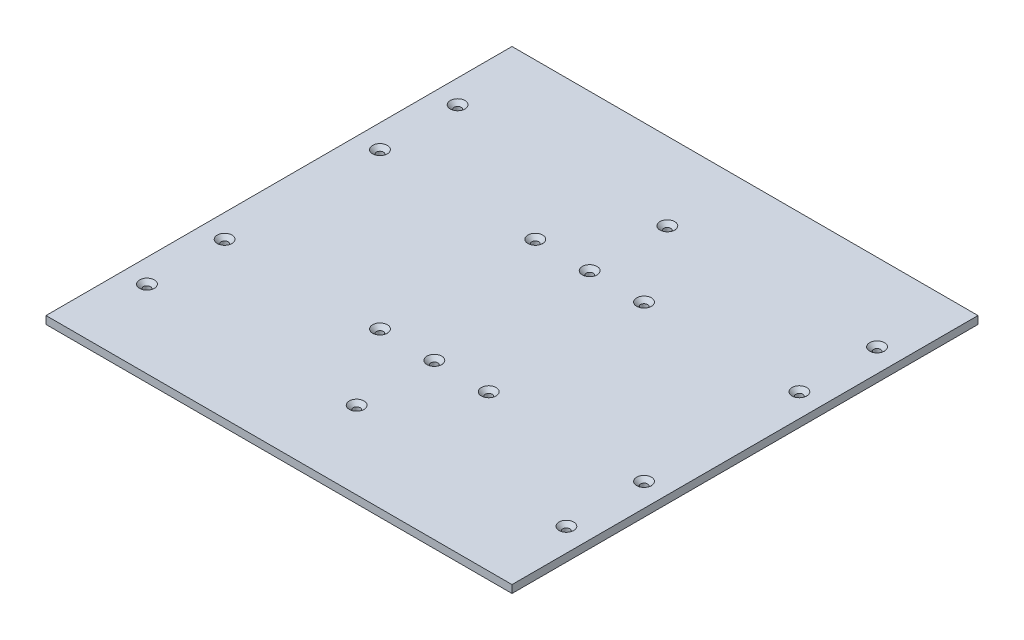
SolidWorks part; units mm, degrees
ref_plane "Front Plane" through (0, 0, 0) normal (0, 0, 1) x (1, 0, 0)
ref_plane "Top Plane" through (0, 0, 0) normal (0, 1, 0) x (1, 0, 0)
ref_plane "Right Plane" through (0, 0, 0) normal (1, 0, 0) x (0, 0, -1)
sketch "Sketch1" plane through (0, 0, 0) normal (0, 0, 1) x (1, 0, 0)
  line L0 (-150, 0) -> (150, 0)
  line L1 (150, 0) -> (150, 5)
  line L2 (150, 5) -> (-150, 5)
  line L3 (-150, 5) -> (-150, 0)
  point P4 (0, 0)
  dimension "D1" = 5
  dimension "D2" = 300
extrude "Boss-Extrude1" add sketch "Sketch1" along normal mid plane 300
sketch "Sketch2" plane through (0, 5, 0) normal (0, 1, 0) x (1, 0, 0)
  line L0 (0, -31.5406) -> (0, 65.4517) construction
  line L1 (150, 150) -> (-150, 150) construction
  line L2 (0, 50) -> (118.609, 50) construction
  line L3 (0, 0) -> (208.773, 0) construction
  circle A0 centre (0, 100) radius 2.25
  circle A1 centre (0, 50) radius 2.25
  circle A2 centre (-35, 50) radius 2.25
  circle A3 centre (35, 50) radius 2.25
  circle A4 centre (0, -100) radius 2.25
  circle A5 centre (-35, -50) radius 2.25
  circle A6 centre (0, -50) radius 2.25
  circle A7 centre (35, -50) radius 2.25
  dimension "D1" = 50
  dimension "D2" = 50
  dimension "D3" = 4.5
  dimension "D4" = 4.5
  dimension "D5" = 35
  dimension "D7" = 4.5
  dimension "D8" = 4.5
  dimension "D6" = 35
extrude "Cut-Extrude1" cut sketch "Sketch2" against normal through all
sketch "Sketch3" plane through (0, 0, 0) normal (0, -1, 0) x (-1, 0, 0)
  line L0 (-135, -150) -> (-135, 150) construction
  line L1 (150, 150) -> (-150, 150) construction
  line L2 (0, -150) -> (0, 150) construction
  line L3 (-150, -150) -> (-150, 150) construction
  line L4 (150, -150) -> (-150, -150) construction
  line L5 (150, -150) -> (150, 150) construction
  circle A0 centre (-135, -100) radius 2.25
  circle A1 centre (-135, -50) radius 2.25
  circle A3 centre (-135, 50) radius 2.25
  circle A4 centre (-135, 100) radius 2.25
  circle A5 centre (135, -100) radius 2.25
  circle A6 centre (135, 50) radius 2.25
  circle A7 centre (135, 100) radius 2.25
  circle A9 centre (135, -50) radius 2.25
  circle A10 centre (-135, 0) radius 2.25 [skipped]
  point P33 (0, 0)
  dimension "D2" = 4.5
  dimension "D3" = 50
  dimension "D7" = 50
  dimension "D1" = 15
  dimension "D5" = 50
  dimension "D6" = 15
  dimension "D8" = 50
  dimension "D9" = 15
  dimension "D4" = 5
extrude "Cut-Extrude2" cut sketch "Sketch3" against normal through all
chamfer "Chamfer1" distance 2.5 angle 45 16 edges at (-135, 5, 102.25) (-135, 5, 52.25) (-135, 5, -97.75) (-135, 5, -47.75) (0, 5, -97.75) (-35, 5, -47.75) (0, 5, -47.75) (35, 5, -47.75) (-35, 5, 47.75) (0, 5, 47.75) (35, 5, 47.75) (0, 5, 97.75) (135, 5, 97.75) (135, 5, 47.75) (135, 5, -102.25) (135, 5, -52.25)
